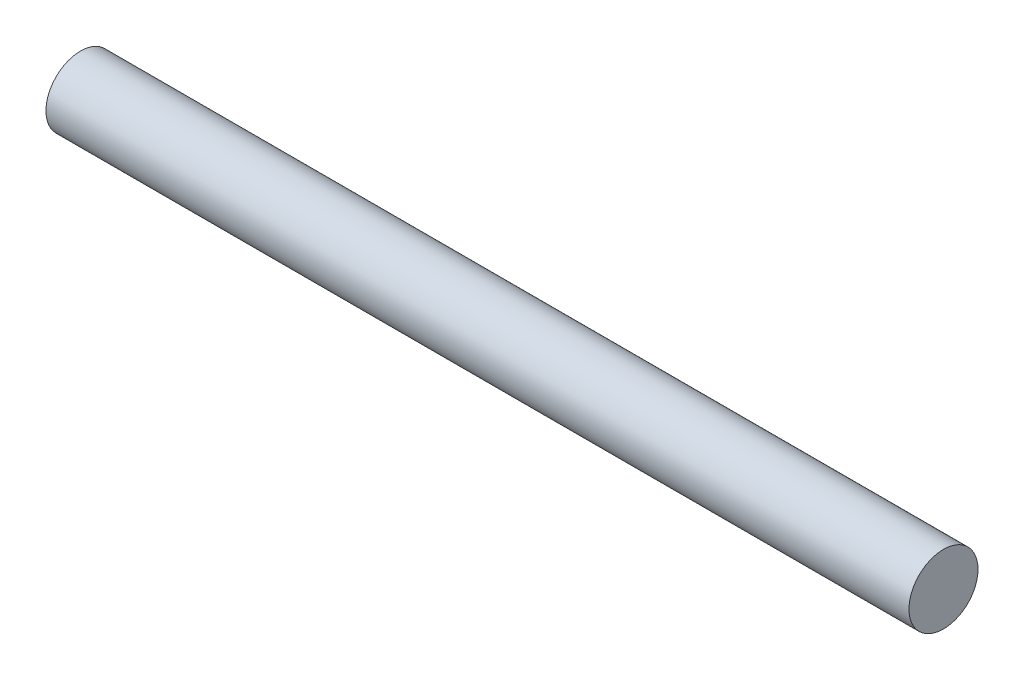
SolidWorks part; units mm, degrees
ref_plane "Front Plane" through (0, 0, 0) normal (0, 0, 1) x (1, 0, 0)
ref_plane "Top Plane" through (0, 0, 0) normal (0, 1, 0) x (1, 0, 0)
ref_plane "Right Plane" through (0, 0, 0) normal (1, 0, 0) x (0, 0, -1)
sketch "Sketch1" plane through (0, 0, 0) normal (1, 0, 0) x (0, 0, -1)
  circle A0 centre (0, 0) radius 4
  dimension "D1" = 8
extrude "Boss-Extrude1" add sketch "Sketch1" along normal blind 100
sketch "Sketch2" plane through (100, 0, 0) normal (1, 0, 0) x (0, 0, -1)
  line L0 (0, 0) -> (0, 4) construction
  line L1 (-0.1999, 3.995) -> (-0.1999, 3.7947)
  line L2 (0.1999, 3.995) -> (0.1999, 3.7947)
  line L3 (2.1864, 3.3495) -> (2.0687, 3.1875)
  line L4 (2.51, 3.1145) -> (2.3922, 2.9525)
  line L5 (3.7377, 1.4247) -> (3.5472, 1.3628)
  line L6 (3.8613, 1.0444) -> (3.6708, 0.9825)
  line L7 (3.8613, -1.0444) -> (3.6708, -0.9825)
  line L8 (3.7377, -1.4247) -> (3.5472, -1.3628)
  line L9 (2.51, -3.1145) -> (2.3922, -2.9525)
  line L10 (2.1864, -3.3495) -> (2.0687, -3.1875)
  line L11 (0.1999, -3.995) -> (0.1999, -3.7947)
  line L12 (-0.1999, -3.995) -> (-0.1999, -3.7947)
  line L13 (-2.1864, -3.3495) -> (-2.0687, -3.1875)
  line L14 (-2.51, -3.1145) -> (-2.3922, -2.9525)
  line L15 (-3.7377, -1.4247) -> (-3.5472, -1.3628)
  line L16 (-3.8613, -1.0444) -> (-3.6708, -0.9825)
  line L17 (-3.8613, 1.0444) -> (-3.6708, 0.9825)
  line L18 (-3.7377, 1.4247) -> (-3.5472, 1.3628)
  line L19 (-2.51, 3.1145) -> (-2.3922, 2.9525)
  line L20 (-2.1864, 3.3495) -> (-2.0687, 3.1875)
  circle A0 centre (0, 0) radius 3.8
  circle A1 centre (0, 0) radius 4 construction
  arc A2 (0, 4) -> (0.1999, 3.995) centre (0, 0) cw
  arc A3 (0, 4) -> (-0.1999, 3.995) centre (0, 0) ccw
  arc A4 (2.3511, 3.2361) -> (2.1864, 3.3495) centre (0, 0) ccw
  arc A5 (2.3511, 3.2361) -> (2.51, 3.1145) centre (0, 0) cw
  arc A6 (3.8042, 1.2361) -> (3.7377, 1.4247) centre (0, 0) ccw
  arc A7 (3.8042, 1.2361) -> (3.8613, 1.0444) centre (0, 0) cw
  arc A8 (3.8042, -1.2361) -> (3.8613, -1.0444) centre (0, 0) ccw
  arc A9 (3.8042, -1.2361) -> (3.7377, -1.4247) centre (0, 0) cw
  arc A10 (2.3511, -3.2361) -> (2.51, -3.1145) centre (0, 0) ccw
  arc A11 (2.3511, -3.2361) -> (2.1864, -3.3495) centre (0, 0) cw
  arc A12 (0, -4) -> (0.1999, -3.995) centre (0, 0) ccw
  arc A13 (0, -4) -> (-0.1999, -3.995) centre (0, 0) cw
  arc A14 (-2.3511, -3.2361) -> (-2.1864, -3.3495) centre (0, 0) ccw
  arc A15 (-2.3511, -3.2361) -> (-2.51, -3.1145) centre (0, 0) cw
  arc A16 (-3.8042, -1.2361) -> (-3.7377, -1.4247) centre (0, 0) ccw
  arc A17 (-3.8042, -1.2361) -> (-3.8613, -1.0444) centre (0, 0) cw
  arc A18 (-3.8042, 1.2361) -> (-3.8613, 1.0444) centre (0, 0) ccw
  arc A19 (-3.8042, 1.2361) -> (-3.7377, 1.4247) centre (0, 0) cw
  arc A20 (-2.3511, 3.2361) -> (-2.51, 3.1145) centre (0, 0) ccw
  arc A21 (-2.3511, 3.2361) -> (-2.1864, 3.3495) centre (0, 0) cw
  circle A22 centre (0, 0) radius 4
  point P59 (0, 0)
  dimension "D1" = 0.2
  dimension "D2" = 0.2
  dimension "D3" = 0.2
  dimension "D4" = 10
